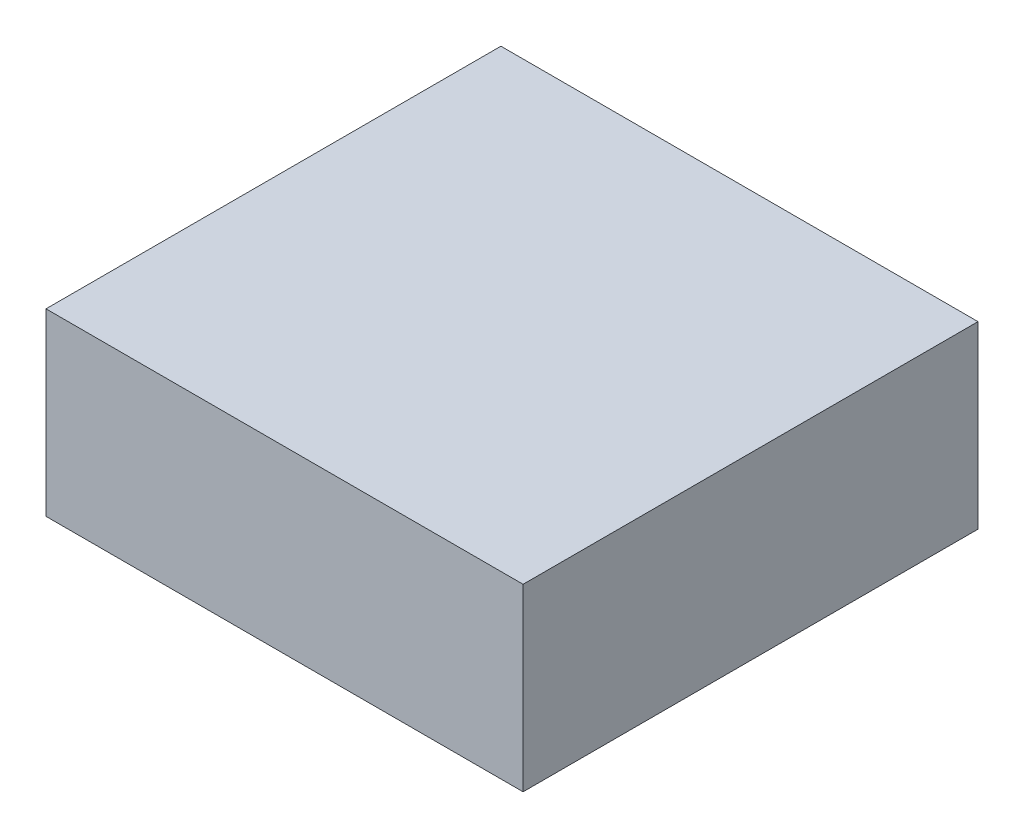
SolidWorks part; units mm, degrees
material "CA"
ref_plane "Alzado" through (0, 0, 0) normal (0, 0, 1) x (1, 0, 0)
ref_plane "Planta" through (0, 0, 0) normal (0, 1, 0) x (1, 0, 0)
ref_plane "Vista lateral" through (0, 0, 0) normal (1, 0, 0) x (0, 0, -1)
sketch "Croquis1" plane through (0, 0, 0) normal (0, 1, 0) x (1, 0, 0)
  line L1 (-215, -205) -> (215, -205)
  line L2 (-215, -205) -> (-215, 205)
  line L3 (-215, 205) -> (215, 205)
  line L4 (215, -205) -> (215, 205)
  line L5 (-215, -205) -> (215, 205) construction
  line L6 (-215, 205) -> (215, -205) construction
  point P0 (0, 0)
  dimension "D1" = 430
  dimension "D2" = 410
extrude "Saliente-Extruir1" add sketch "Croquis1" along normal blind 162
